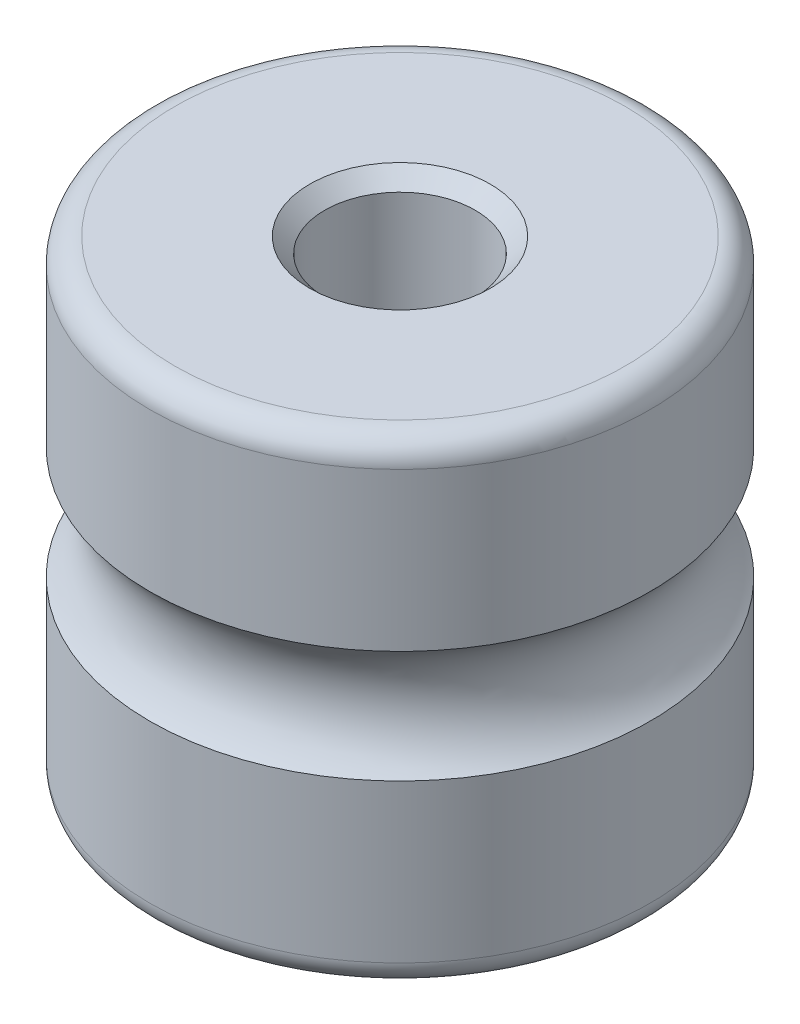
SolidWorks part; units mm, degrees
ref_plane "前视基准面" through (0, 0, 0) normal (0, 0, 1) x (1, 0, 0)
ref_plane "上视基准面" through (0, 0, 0) normal (0, 1, 0) x (1, 0, 0)
ref_plane "右视基准面" through (0, 0, 0) normal (1, 0, 0) x (0, 0, -1)
other "Configuration Table"
sketch "草图1" plane through (0, 513.97, 0) normal (0, 1, 0) x (1, 0, 0)
  circle A0 centre (-989.2914, 54.73) radius 49.855
extrude "凸台-拉伸1" add sketch "草图1" along normal up to surface (95.18 mm away)
sketch "草图2" plane through (0, 609.15, 0) normal (0, 1, 0) x (1, 0, 0)
  point P0 (-989.2914, 54.73)
  point P1 (0, 0)
ref_plane "基准面1" through (0, 0, 10) normal (0, 0, 1) x (1, 0, 0)
ref_plane "基准面2" through (0, 0, -54.73) normal (0, 0, 1) x (1, 0, 0)
sketch "草图3" plane through (0, 0, -54.73) normal (0, 0, 1) x (1, 0, 0)
  line L0 (-1039.1464, 561.56) -> (-1049.1464, 561.56) construction
  line L1 (-1039.1464, 609.15) -> (-1039.1464, 513.97) construction
  line L2 (-989.2914, 609.15) -> (-989.2914, 471.2525) construction
  circle A0 centre (-1049.1464, 561.56) radius 15
  dimension "D2" = 30
  dimension "D1" = 10
revolve "切除-旋转1" cut sketch "草图3" angle 360 about L2
sketch "草图4" plane through (0, 609.15, 0) normal (0, 1, 0) x (1, 0, 0)
  circle A0 centre (-989.2914, 54.73) radius 15
  dimension "D1" = 30
extrude "切除-拉伸1" cut sketch "草图4" against normal mid plane 500
chamfer "倒角1" distance 3 angle 45 2 edges at (-989.2914, 513.97, -39.73) (-989.2914, 609.15, -39.73)
fillet "圆角1" radius 5 2 edges at (-989.2914, 513.97, -4.875) (-989.2914, 609.15, -4.875)
